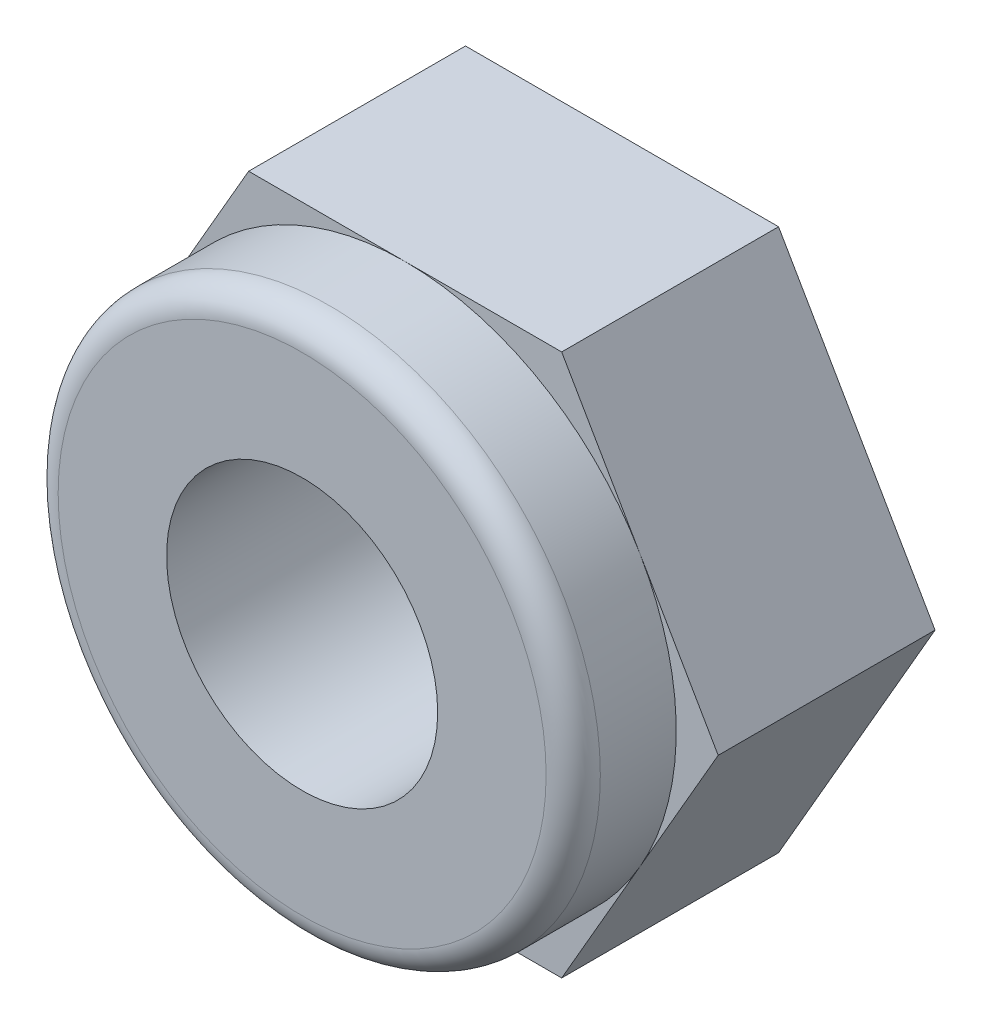
SolidWorks part; units mm, degrees
ref_plane "前视基准面" through (0, 0, 0) normal (0, 0, 1) x (1, 0, 0)
ref_plane "上视基准面" through (0, 0, 0) normal (0, 1, 0) x (1, 0, 0)
ref_plane "右视基准面" through (0, 0, 0) normal (1, 0, 0) x (0, 0, -1)
sketch "草图1" plane through (0, 0, 0) normal (0, 0, 1) x (1, 0, 0)
  line L1 (5.7735, 0) -> (2.8868, 5)
  line L2 (2.8868, 5) -> (-2.8868, 5)
  line L3 (-2.8868, 5) -> (-5.7735, 0)
  line L4 (-5.7735, 0) -> (-2.8868, -5)
  line L5 (-2.8868, -5) -> (2.8868, -5)
  line L6 (2.8868, -5) -> (5.7735, 0)
  circle A0 centre (0, 0) radius 5 construction
  dimension "D1" = 10
extrude "凸台-拉伸1" add sketch "草图1" along normal blind 4
sketch "草图2" plane through (0, 0, 4) normal (0, 0, 1) x (1, 0, 0)
  circle A0 centre (0, 0) radius 5
  dimension "D1" = 10
extrude "凸台-拉伸2" add sketch "草图2" along normal blind 1.9
hole_wizard "M6 螺纹孔1" positions "草图5" profile "草图6" tap size "M6" standard "GB" end condition through all
sketch "草图5" plane through (0, 0, 5.9) normal (0, 0, 1) x (1, 0, 0)
  point P0 (0, 0)
  point P3 (0, 0)
sketch "草图6" plane through (0, 0, 5.9) normal (1, 0, 0) x (0, -1, 0)
  line L0 (0, 0) -> (0, 5.9)
  line L1 (0, 5.9) -> (2.5, 5.9)
  line L2 (2.5, 5.9) -> (2.5, 0)
  line L5 (2.5, 0) -> (0, 0)
  line L11 (0, -6.35) -> (0, 107.95) construction
  dimension "通孔螺纹孔钻头直径" = 5
  dimension "通孔螺纹孔钻头深度" = 5.9
cosmetic thread "孔螺蚊线2" parameters "D2"=6
fillet "圆角1" radius 0.5 1 edges at (5, 0, 5.9)
